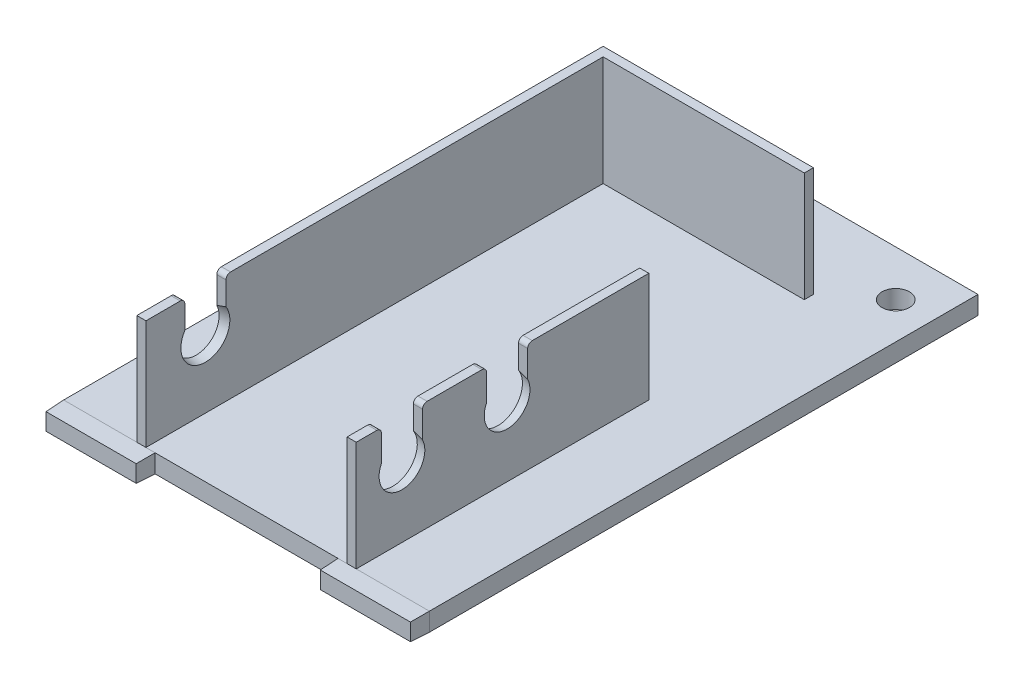
SolidWorks part; units mm, degrees
ref_plane "Front Plane" through (0, 0, 0) normal (0, 0, 1) x (1, 0, 0)
ref_plane "Top Plane" through (0, 0, 0) normal (0, 1, 0) x (1, 0, 0)
ref_plane "Right Plane" through (0, 0, 0) normal (1, 0, 0) x (0, 0, -1)
sketch "Sketch1" plane through (0, 0, 0) normal (1, 0, 0) x (0, 0, -1)
  line L1 (0, 0) -> (-60, 0)
  dimension "D1" = 60
extrude "Extrude-Thin1" add sketch "Sketch1" along normal mid plane 40 thin
sketch "Sketch2" plane through (0, 2, 0) normal (0, 1, 0) x (1, 0, 0)
  line L0 (20, 0) -> (20, -60) construction
  line L1 (11, -60) -> (-11, -60) construction
  line L2 (11, -60) -> (11, -10) construction
  line L3 (11, -10) -> (-11, -10) construction
  line L4 (-11, -60) -> (-11, -10) construction
  line L5 (11, -60) -> (-11, -10) construction
  line L6 (11, -10) -> (-11, -60) construction
  line L8 (11, -60) -> (11, -28)
  line L9 (11, -10) -> (-11, -10)
  line L10 (-11, -10) -> (-11, -60)
  line L12 (20, -60) -> (-20, -60) construction
  point P0 (0, -35)
  point P8 (-11, -60)
  dimension "D1" = 9
  dimension "D2" = 32
  dimension "D3" = 50
  dimension "D4" = 22
extrude "Extrude-Thin2" add sketch "Sketch2" along normal blind 12 thin
sketch "Sketch3" plane through (0, 2, 0) normal (0, 1, 0) x (1, 0, 0)
  line L0 (-16, -5) -> (-20, -5) construction
  line L3 (-20, 0) -> (-20, -60) construction
  line L4 (16, -5) -> (20, -5) construction
  line L5 (20, 0) -> (20, -60) construction
  line L6 (20, 0) -> (-20, 0) construction
  circle A0 centre (-16, -5) radius 1.5
  circle A1 centre (16, -5) radius 1.5
  point P10 (0, 0)
  point P11 (0, 0)
  dimension "D1" = 3
  dimension "D2" = 3
  dimension "D3" = 5
  dimension "D4" = 4
extrude "Cut-Extrude1" cut sketch "Sketch3" against normal through all
sketch "Sketch4" plane through (0, 0, 60) normal (0, 0, 1) x (1, 0, 0)
  line L0 (-12, 2) -> (-20, 2) construction
  line L1 (-20, 2) -> (-10, 2)
  line L2 (-20, 2) -> (-20, 0)
  line L3 (-20, 0) -> (-10, 0)
  line L4 (-10, 2) -> (-10, 0)
  line L5 (20, 0) -> (-20, 0) construction
  line L6 (11, 2) -> (-11, 2) construction
  line L7 (10, 2) -> (20, 2)
  line L8 (10, 2) -> (10, 0)
  line L9 (10, 0) -> (20, 0)
  line L10 (20, 2) -> (20, 0)
  line L11 (-20, 2) -> (-10, 0) construction
  line L12 (10, 2) -> (20, 0) construction
  line L13 (15, 1) -> (-15, 1) construction
  point P14 (-15, 1)
  point P15 (15, 1)
  point P18 (0, 1)
  dimension "D1" = 10
  dimension "D2" = 30
extrude "Boss-Extrude1" add sketch "Sketch4" along normal blind 2 draft 2
sketch "Sketch6" plane through (12, 0, 0) normal (1, 0, 0) x (0, 0, -1)
  line L0 (0, 2) -> (-60, 2) construction
  line L1 (-60, 14) -> (-60, 2) construction
  circle A0 centre (-55, 9.5) radius 2.5
  circle A1 centre (-43.5, 9.5) radius 2.5
  point P6 (0, 0)
  point P9 (0, 0)
  dimension "D2" = 5
  dimension "D1" = 7.5
  dimension "D3" = 5
  dimension "D4" = 16.5
sketch "Sketch7" plane through (-12, 0, 0) normal (-1, 0, 0) x (0, 0, 1)
  line L0 (60, 14) -> (60, 2) construction
  line L1 (9, 2) -> (60, 2) construction
  circle A0 centre (53.5, 9.5) radius 2.5
  circle A1 centre (55, 9.5) radius 2.5 construction
  dimension "D1" = 6.5
  dimension "D2" = 7.5
extrude "Cut-Extrude4" cut sketch "Sketch6" against normal up to next (1 mm away) draft 10 draft outward yes
extrude "Cut-Extrude6" cut sketch "Sketch7" against normal up to next (1 mm away) draft 10 draft outward yes
sketch "Sketch8" plane through (12, 0, 0) normal (1, 0, 0) x (0, 0, -1)
  line L1 (-57.25, 15.5173) -> (-52.75, 15.5173)
  line L2 (-57.25, 15.5173) -> (-57.25, 9.4663)
  line L3 (-57.25, 9.4663) -> (-52.75, 9.4663)
  line L4 (-52.75, 15.5173) -> (-52.75, 9.4663)
  line L5 (-57.25, 15.5173) -> (-52.75, 9.4663) construction
  line L6 (-57.25, 9.4663) -> (-52.75, 15.5173) construction
  line L7 (-45.75, 15.486) -> (-41.25, 15.486)
  line L8 (-45.75, 15.486) -> (-45.75, 9.435)
  line L9 (-45.75, 9.435) -> (-41.25, 9.435)
  line L10 (-41.25, 15.486) -> (-41.25, 9.435)
  line L11 (-45.75, 15.486) -> (-41.25, 9.435) construction
  line L12 (-45.75, 9.435) -> (-41.25, 15.486) construction
  point P0 (-55, 12.4918)
  point P5 (-43.5, 12.4605)
  point P10 (-53.5493, 9.337)
  point P11 (0, 0)
  point P13 (0, 0)
  point P15 (-53.8596, 9.5)
  point P16 (-43.5, 12.4918)
  point P17 (-45.7086, 9.435)
  dimension "D1" = 4.5
extrude "Cut-Extrude7" cut sketch "Sketch8" against normal up to next
sketch "Sketch9" plane through (-12, 0, 0) normal (-1, 0, 0) x (0, 0, 1)
  line L1 (51.25, 15.976) -> (55.75, 15.976)
  line L2 (51.25, 15.976) -> (51.25, 10.1899)
  line L3 (51.25, 10.1899) -> (55.75, 10.1899)
  line L4 (55.75, 15.976) -> (55.75, 10.1899)
  line L5 (51.25, 15.976) -> (55.75, 10.1899) construction
  line L6 (51.25, 10.1899) -> (55.75, 15.976) construction
  point P0 (53.5, 13.0829)
  point P5 (0, 0)
  dimension "D1" = 4.5
extrude "Cut-Extrude8" cut sketch "Sketch9" against normal up to next
fillet "Fillet1" radius 0.5 6 edges at (11.5, 14, 45.75) (11.5, 14, 41.25) (11.5, 14, 52.75) (11.5, 14, 57.25) (-11.5, 14, 51.25) (-11.5, 14, 55.75)
